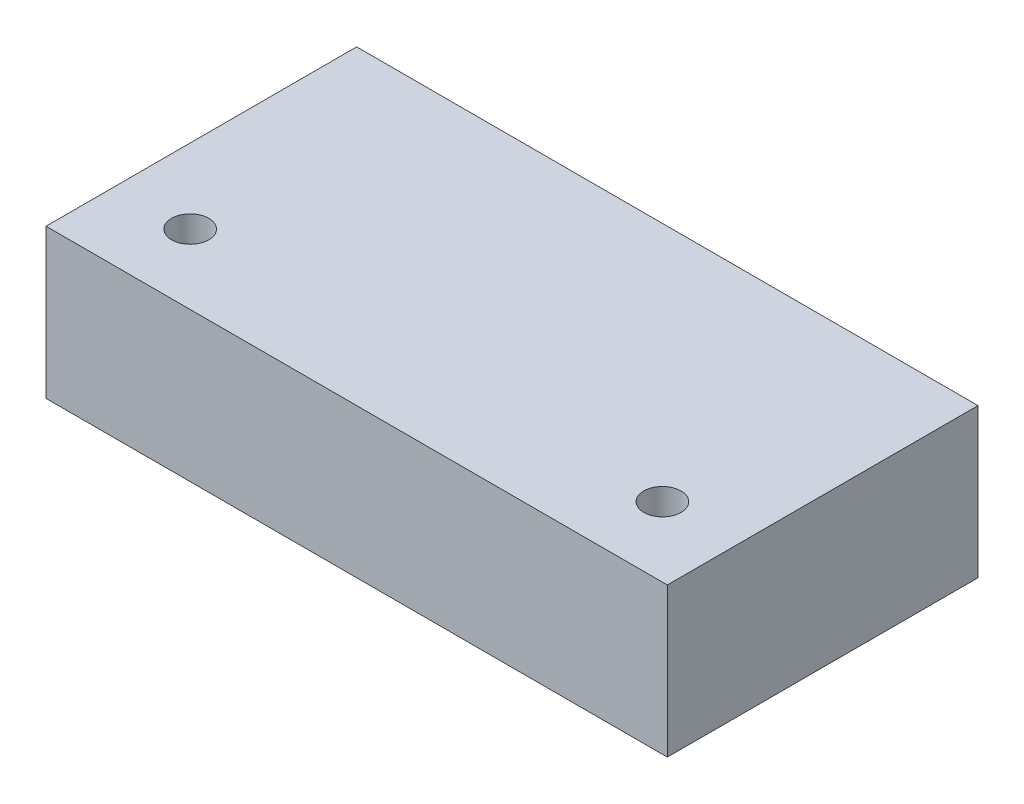
SolidWorks part; units mm, degrees
ref_plane "Front Plane" through (0, 0, 0) normal (0, 0, 1) x (1, 0, 0)
ref_plane "Top Plane" through (0, 0, 0) normal (0, 1, 0) x (1, 0, 0)
ref_plane "Right Plane" through (0, 0, 0) normal (1, 0, 0) x (0, 0, -1)
sketch "Sketch1" plane through (0, 0, 0) normal (0, 0, 1) x (1, 0, 0)
  line L1 (-25, 6) -> (25, 6)
  line L2 (-25, 6) -> (-25, -6)
  line L3 (-25, -6) -> (25, -6)
  line L4 (25, 6) -> (25, -6)
  line L5 (-25, 6) -> (25, -6) construction
  line L6 (-25, -6) -> (25, 6) construction
  point P0 (0, 0)
  dimension "D1" = 12
  dimension "D2" = 50
extrude "Boss-Extrude1" add sketch "Sketch1" along normal blind 25
sketch "Sketch2" plane through (0, -6, 0) normal (0, -1, 0) x (1, 0, 0)
  line L0 (0, 0) -> (0, 25) construction
  line L1 (-25, 0) -> (25, 0) construction
  line L2 (-25, 25) -> (25, 25) construction
  line L3 (-19, 19.3959) -> (19, 19.3959) construction
  circle A0 centre (-19, 19.3959) radius 1.5
  circle A1 centre (19, 19.3959) radius 1.5
  point P8 (0, 19.3959)
  dimension "D1" = 3
  dimension "D2" = 38
extrude "Cut-Extrude1" cut sketch "Sketch2" against normal up to next
